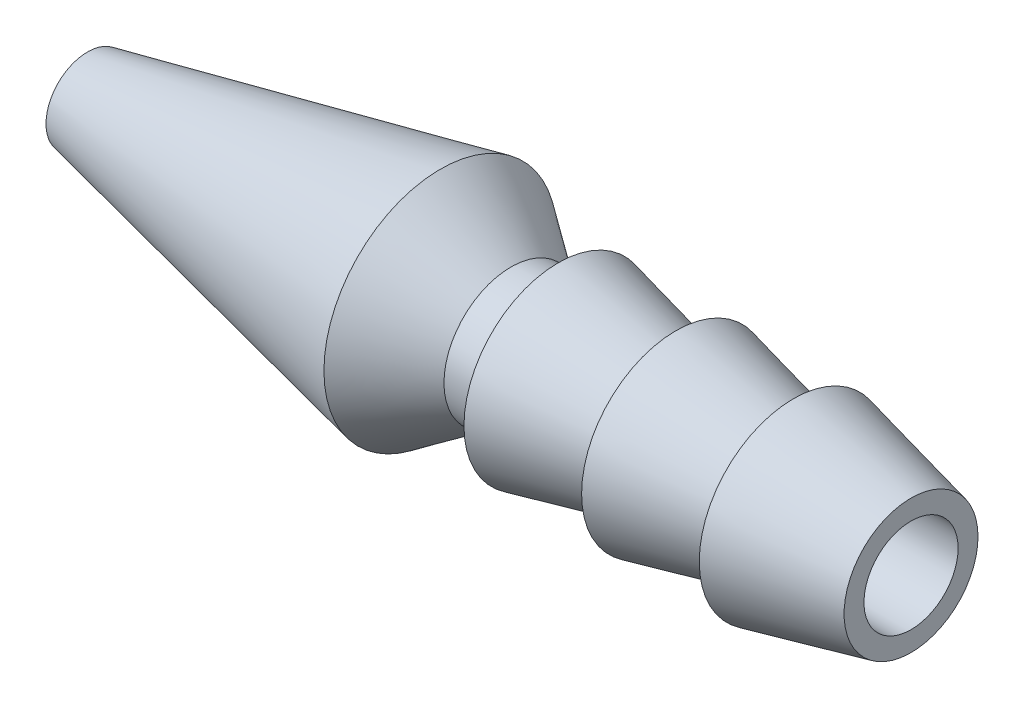
SolidWorks part; units mm, degrees
ref_plane "Front Plane" through (0, 0, 0) normal (0, 0, 1) x (1, 0, 0)
ref_plane "Top Plane" through (0, 0, 0) normal (0, 1, 0) x (1, 0, 0)
ref_plane "Right Plane" through (0, 0, 0) normal (1, 0, 0) x (0, 0, -1)
sketch "Sketch1" plane through (0, 0, 0) normal (1, 0, 0) x (0, 0, -1)
  circle A0 centre (0, 0) radius 4
extrude "Boss-Extrude1" add sketch "Sketch1" along normal blind 5 draft 13
sketch "Sketch2" plane through (5, 0, 0) normal (1, 0, 0) x (0, 0, -1)
  circle A0 centre (0, 0) radius 4
extrude "Boss-Extrude2" add sketch "Sketch2" along normal blind 5 draft 13
sketch "Sketch3" plane through (10, 0, 0) normal (1, 0, 0) x (0, 0, -1)
  circle A0 centre (0, 0) radius 4
extrude "Boss-Extrude3" add sketch "Sketch3" along normal blind 5 draft 13
sketch "Sketch4" plane through (0, 0, 0) normal (-1, 0, 0) x (0, 0, 1)
  circle A0 centre (0, 0) radius 2.85
extrude "Boss-Extrude4" add sketch "Sketch4" along normal blind 2
sketch "Sketch5" plane through (-2, 0, 0) normal (-1, 0, 0) x (0, 0, 1)
  circle A0 centre (0, 0) radius 2.85
extrude "Boss-Extrude5" add sketch "Sketch5" along normal blind 3 draft 35 draft outward yes
sketch "Sketch6" plane through (-5, 0, 0) normal (-1, 0, 0) x (0, 0, 1)
  circle A0 centre (0, 0) radius 4.9506
extrude "Boss-Extrude6" add sketch "Sketch6" along normal blind 15 draft 12
sketch "Sketch9" plane through (15, 0, 0) normal (1, 0, 0) x (0, 0, -1)
  circle A0 centre (0, 0) radius 2
extrude "Cut-Extrude1" cut sketch "Sketch9" against normal blind 20
